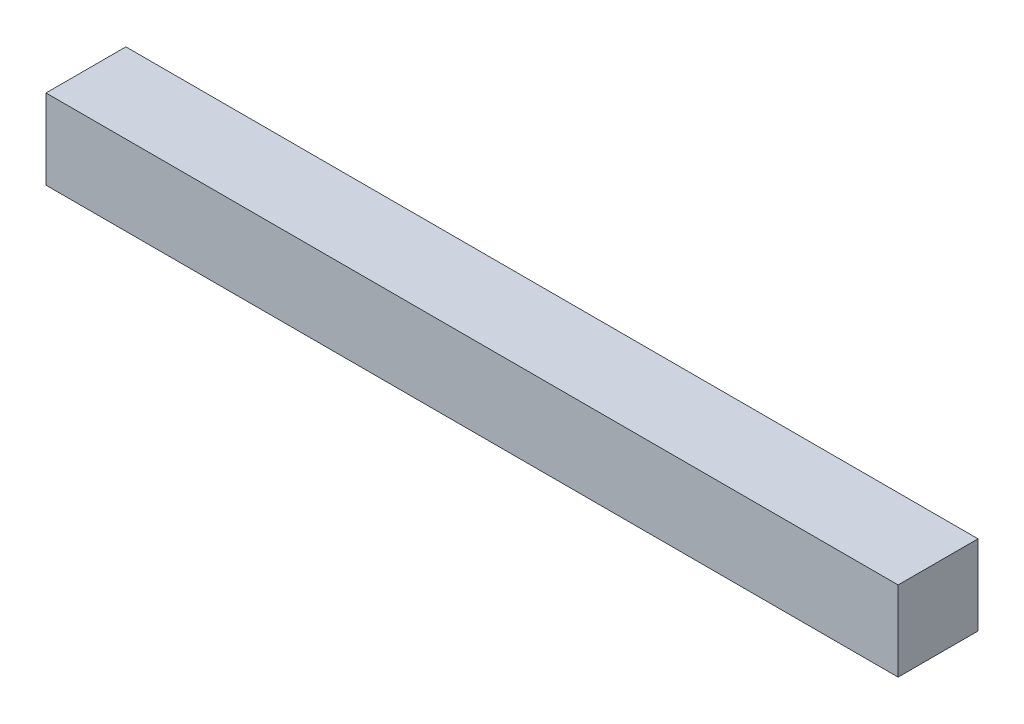
SolidWorks part; units mm, degrees
ref_plane "Front Plane" through (0, 0, 0) normal (0, 0, 1) x (1, 0, 0)
ref_plane "Top Plane" through (0, 0, 0) normal (0, 1, 0) x (1, 0, 0)
ref_plane "Right Plane" through (0, 0, 0) normal (1, 0, 0) x (0, 0, -1)
sketch "Sketch1" plane through (0, 0, 0) normal (1, 0, 0) x (0, 0, -1)
  line L1 (0, 0) -> (38.1, 0)
  line L2 (0, 0) -> (0, -38.1)
  line L3 (0, -38.1) -> (38.1, -38.1)
  line L4 (38.1, 0) -> (38.1, -38.1)
  dimension "D1" = 38.1
  dimension "D2" = 38.1
extrude "Boss-Extrude1" add sketch "Sketch1" along normal blind 406.4
